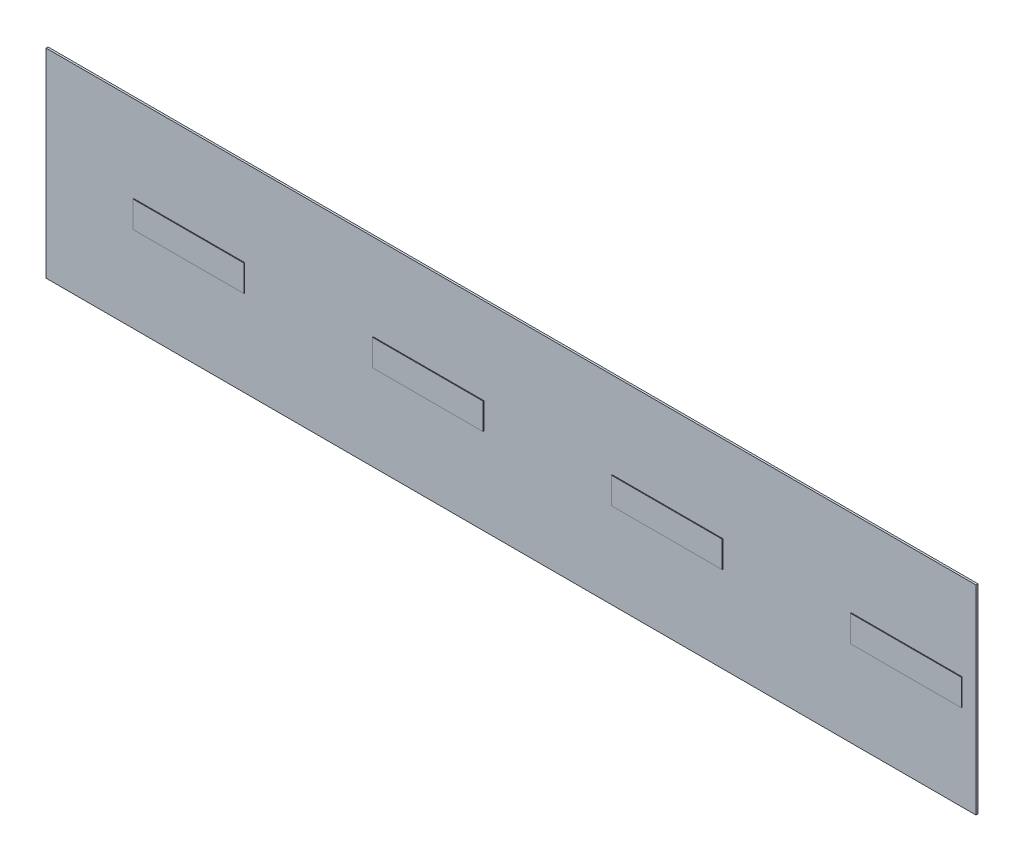
SolidWorks part; units mm, degrees
ref_plane "Front Plane" through (0, 0, 0) normal (0, 0, 1) x (1, 0, 0)
ref_plane "Top Plane" through (0, 0, 0) normal (0, 1, 0) x (1, 0, 0)
ref_plane "Right Plane" through (0, 0, 0) normal (1, 0, 0) x (0, 0, -1)
sketch "Sketch1" plane through (0, 0, 0) normal (0, 0, 1) x (1, 0, 0)
  line L1 (0, 0) -> (700, 0)
  line L2 (0, 0) -> (0, 150)
  line L3 (0, 150) -> (700, 150)
  line L4 (700, 0) -> (700, 150)
  dimension "D1" = 150
  dimension "D2" = 700
extrude "Boss-Extrude1" add sketch "Sketch1" along normal blind 1.5
sketch "Sketch2" plane through (0, 0, 1.5) normal (0, 0, 1) x (1, 0, 0)
  line L0 (246.1651, 65.0625) -> (246.1651, 84.9375)
  line L3 (246.1651, 65.0625) -> (329.5234, 65.0625)
  line L8 (66.1651, 65.0625) -> (149.5234, 65.0625)
  line L9 (66.1651, 65.0625) -> (66.1651, 84.9375)
  line L10 (66.1651, 84.9375) -> (149.5234, 84.9375)
  line L11 (149.5234, 65.0625) -> (149.5234, 84.9375)
  line L12 (66.1651, 65.0625) -> (149.5234, 84.9375) construction
  line L13 (66.1651, 84.9375) -> (149.5234, 65.0625) construction
  line L14 (329.5234, 65.0625) -> (329.5234, 84.9375)
  line L15 (246.1651, 84.9375) -> (329.5234, 84.9375)
  line L16 (426.1651, 65.0625) -> (426.1651, 84.9375)
  line L17 (426.1651, 65.0625) -> (509.5234, 65.0625)
  line L18 (509.5234, 65.0625) -> (509.5234, 84.9375)
  line L19 (426.1651, 84.9375) -> (509.5234, 84.9375)
  line L20 (606.1651, 65.0625) -> (606.1651, 84.9375)
  line L21 (606.1651, 65.0625) -> (689.5234, 65.0625)
  line L22 (689.5234, 65.0625) -> (689.5234, 84.9375)
  line L23 (606.1651, 84.9375) -> (689.5234, 84.9375)
  point P6 (107.8443, 75)
  dimension "D1" = 4
extrude "Boss-Extrude2" add sketch "Sketch2" along normal blind 0.6
